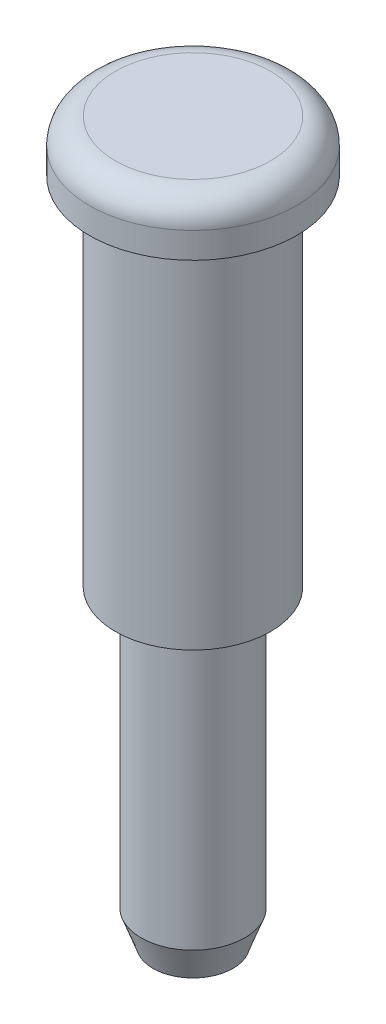
SolidWorks part; units mm, degrees
ref_plane "Plano frontal" through (0, 0, 0) normal (0, 0, 1) x (1, 0, 0)
ref_plane "Plano superior" through (0, 0, 0) normal (0, 1, 0) x (1, 0, 0)
ref_plane "Plano direito" through (0, 0, 0) normal (1, 0, 0) x (0, 0, -1)
sketch "Esboço1" plane through (0, 0, 0) normal (0, 0, 1) x (1, 0, 0)
  line L0 (0, -53.198) -> (0, 31.5) construction
  line L1 (0, 31.5) -> (8, 31.5)
  line L2 (8, 31.5) -> (8, 27.5)
  line L3 (8, 27.5) -> (6, 27.5)
  line L4 (6, 27.5) -> (6, 0)
  line L5 (6, 0) -> (4, 0)
  line L6 (4, 0) -> (4, -21.5)
  line L7 (4, -21.5) -> (3.0901, -24)
  line L8 (3.0901, -24) -> (0, -24)
  line L9 (0, -24) -> (0, 31.5)
  dimension "D1" = 8
  dimension "D2" = 6
  dimension "D3" = 4
  dimension "D4" = 20
  dimension "D5" = 2.5
  dimension "D6" = 24
  dimension "D7" = 27.5
  dimension "D8" = 4
revolve "Revolução1" add sketch "Esboço1" angle 360 about L0
fillet "Filete1" radius 2 1 edges at (8, 31.5, 0)
